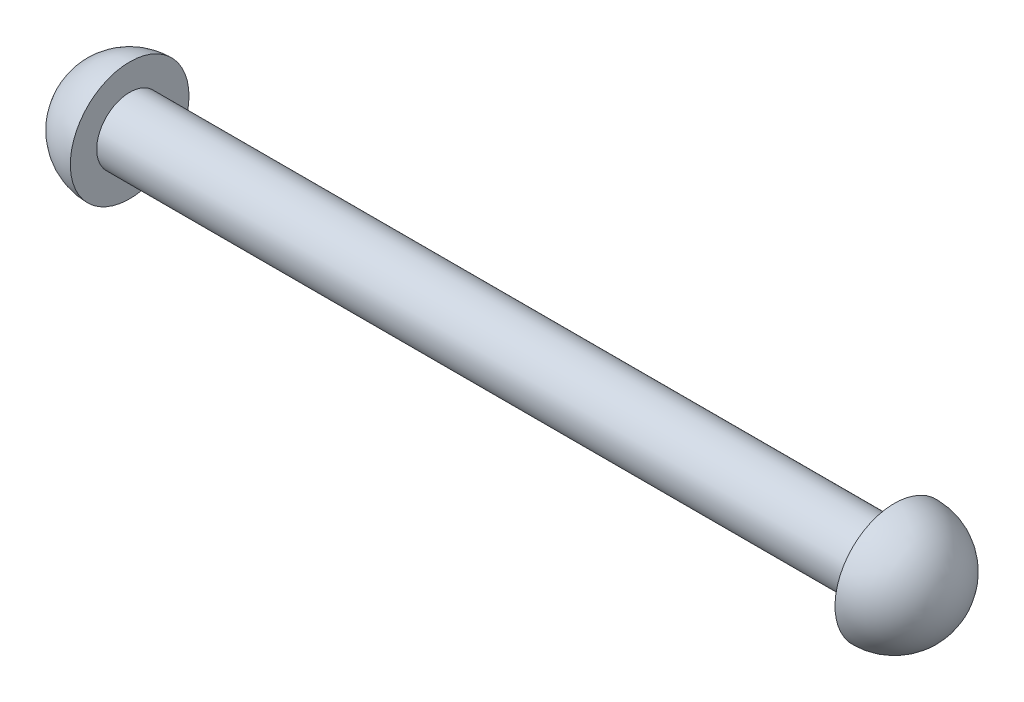
SolidWorks part; units mm, degrees
material "AISI 1020"
ref_plane "Front Plane" through (0, 0, 0) normal (0, 0, 1) x (1, 0, 0)
ref_plane "Top Plane" through (0, 0, 0) normal (0, 1, 0) x (1, 0, 0)
ref_plane "Right Plane" through (0, 0, 0) normal (1, 0, 0) x (0, 0, -1)
sketch "Sketch1" plane through (0, 0, 0) normal (0, 0, 1) x (1, 0, 0)
  line L0 (46.1455, 0) -> (0, 0) construction
  line L1 (0, 0) -> (0, 22.349) construction
  line L2 (-36.83, 3.175) -> (36.83, 3.175)
  line L3 (36.83, 3.175) -> (36.83, 5.715)
  line L4 (-36.83, 3.175) -> (-36.83, 5.715)
  line L5 (42.545, 0) -> (-42.545, 0)
  arc A0 (36.83, 5.715) -> (42.545, 0) centre (36.83, 0) cw
  arc A1 (-36.83, 5.715) -> (-42.545, 0) centre (-36.83, 0) ccw
  point P9 (0, 0)
  point P10 (46.1455, 0)
  point P15 (0, 3.175)
  dimension "D3" = 5.715
  dimension "D1" = 6.35
  dimension "D2" = 73.66
revolve "Revolve1" add sketch "Sketch1" angle 360 about L5
